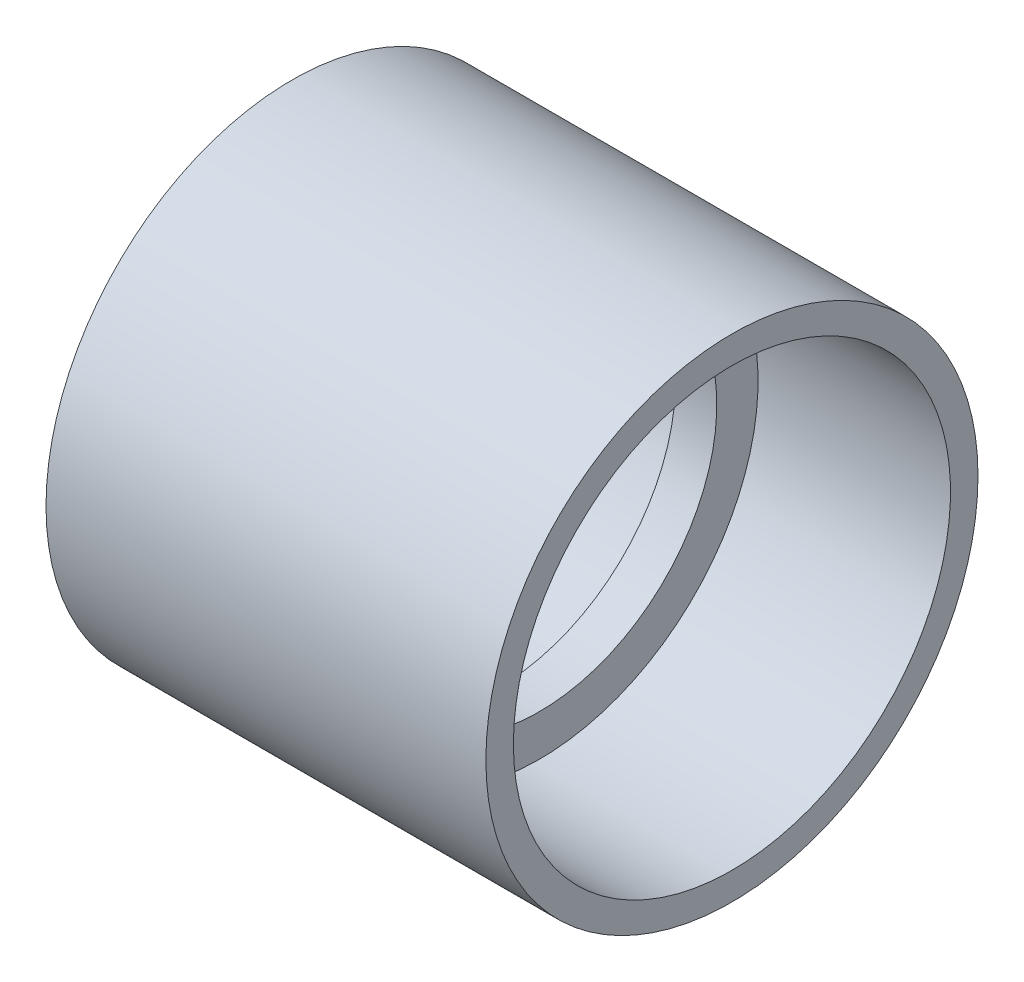
SolidWorks part; units mm, degrees
ref_plane "Front Plane" through (0, 0, 0) normal (0, 0, 1) x (1, 0, 0)
ref_plane "Top Plane" through (0, 0, 0) normal (0, 1, 0) x (1, 0, 0)
ref_plane "Right Plane" through (0, 0, 0) normal (1, 0, 0) x (0, 0, -1)
sketch "Sketch1" plane through (0, 0, 0) normal (0, 1, 0) x (1, 0, 0)
  line L0 (3, 15.9) -> (17, 15.9)
  line L1 (-15, 15.9) -> (0, 15.9)
  line L2 (-15, 15.9) -> (-15, 17.9)
  line L3 (-15, 17.9) -> (17, 17.9)
  line L4 (17, 15.9) -> (17, 17.9)
  line L5 (0, 12.9) -> (3, 12.9)
  line L6 (0, 12.9) -> (0, 15.9)
  line L8 (3, 12.9) -> (3, 15.9)
  line L9 (0, 0) -> (0, 12.9) construction
  line L10 (-15, 0) -> (18.1531, 0) construction
  dimension "D1" = 15.9
  dimension "D2" = 3
  dimension "D3" = 3
  dimension "D4" = 14
  dimension "D5" = 15
  dimension "D6" = 2
revolve "Revolve1" add sketch "Sketch1" angle 360 about L10
